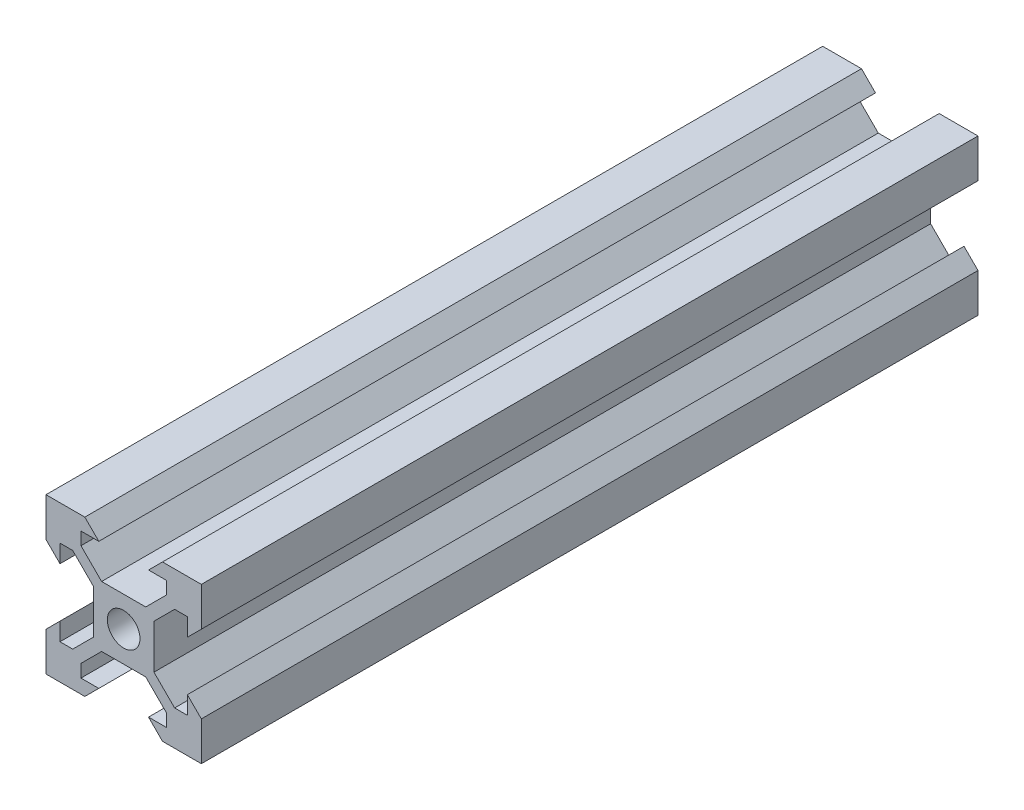
SolidWorks part; units mm, degrees
ref_plane "Front Plane" through (0, 0, 0) normal (0, 0, 1) x (1, 0, 0)
ref_plane "Top Plane" through (0, 0, 0) normal (0, 1, 0) x (1, 0, 0)
ref_plane "Right Plane" through (0, 0, 0) normal (1, 0, 0) x (0, 0, -1)
sketch "Sketch1" plane through (0, 0, 0) normal (0, 0, 1) x (1, 0, 0)
  line L0 (-10, 10) -> (-10, 5)
  line L1 (-10, 5) -> (-8.2, 3.2)
  line L2 (-8.2, 3.2) -> (-8.2, 5.4993)
  line L3 (-8.2, 5.4993) -> (-6.56, 5.4993)
  line L4 (-6.56, 5.4993) -> (-3.9007, 2.84)
  line L5 (-3.9007, 2.84) -> (-3.9007, -2.84)
  line L6 (-3.9007, -2.84) -> (-6.56, -5.4993)
  line L7 (-6.56, -5.4993) -> (-8.2, -5.4993)
  line L8 (-8.2, -5.4993) -> (-8.2, -3.2)
  line L9 (-8.2, -3.2) -> (-10, -5)
  line L10 (-10, -5) -> (-10, -10)
  line L11 (-10, -10) -> (-5, -10)
  line L12 (-5, -10) -> (-3.2, -8.2)
  line L13 (-3.2, -8.2) -> (-5.4993, -8.2)
  line L14 (-5.4993, -8.2) -> (-5.4993, -6.56)
  line L15 (-5.4993, -6.56) -> (-2.84, -3.9007)
  line L16 (-2.84, -3.9007) -> (2.84, -3.9007)
  line L17 (2.84, -3.9007) -> (5.4993, -6.56)
  line L18 (5.4993, -6.56) -> (5.4993, -8.2)
  line L19 (5.4993, -8.2) -> (3.2, -8.2)
  line L20 (3.2, -8.2) -> (5, -10)
  line L21 (5, -10) -> (10, -10)
  line L22 (10, -10) -> (10, -5)
  line L23 (10, -5) -> (8.2, -3.2)
  line L24 (8.2, -3.2) -> (8.2, -5.4993)
  line L25 (8.2, -5.4993) -> (6.56, -5.4993)
  line L26 (6.56, -5.4993) -> (3.9007, -2.84)
  line L27 (3.9007, -2.84) -> (3.9007, 2.84)
  line L28 (3.9007, 2.84) -> (6.56, 5.4993)
  line L29 (6.56, 5.4993) -> (8.2, 5.4993)
  line L30 (8.2, 5.4993) -> (8.2, 3.2)
  line L31 (8.2, 3.2) -> (10, 5)
  line L32 (10, 5) -> (10, 10)
  line L33 (10, 10) -> (5, 10)
  line L34 (5, 10) -> (3.2, 8.2)
  line L35 (3.2, 8.2) -> (5.4993, 8.2)
  line L36 (5.4993, 8.2) -> (5.4993, 6.56)
  line L37 (5.4993, 6.56) -> (2.84, 3.9007)
  line L38 (2.84, 3.9007) -> (-2.84, 3.9007)
  line L39 (-2.84, 3.9007) -> (-5.4993, 6.56)
  line L40 (-5.4993, 6.56) -> (-5.4993, 8.2)
  line L41 (-5.4993, 8.2) -> (-3.2, 8.2)
  line L42 (-3.2, 8.2) -> (-5, 10)
  line L43 (-5, 10) -> (-10, 10)
  circle A0 centre (0, 0) radius 2.1
extrude "Boss-Extrude1" add sketch "Sketch1" against normal blind 100
ref_plane "基准面1" through (0, 0, 0) normal (0, 0, 1) x (1, 0, 0)
